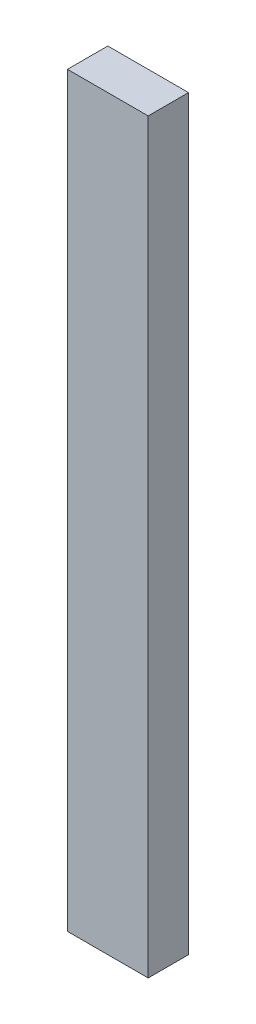
SolidWorks part; units mm, degrees
ref_plane "Front Plane" through (0, 0, 0) normal (0, 0, 1) x (1, 0, 0)
ref_plane "Top Plane" through (0, 0, 0) normal (0, 1, 0) x (1, 0, 0)
ref_plane "Right Plane" through (0, 0, 0) normal (1, 0, 0) x (0, 0, -1)
sketch "Sketch1" plane through (0, 0, 0) normal (0, 1, 0) x (1, 0, 0)
  line L1 (-237.3333, 75) -> (-197.3333, 75)
  line L2 (-237.3333, 75) -> (-237.3333, 55)
  line L3 (-237.3333, 55) -> (-197.3333, 55)
  line L4 (-197.3333, 75) -> (-197.3333, 55)
  dimension "D1" = 40
  dimension "D2" = 20
extrude "Boss-Extrude1" add sketch "Sketch1" along normal blind 370
